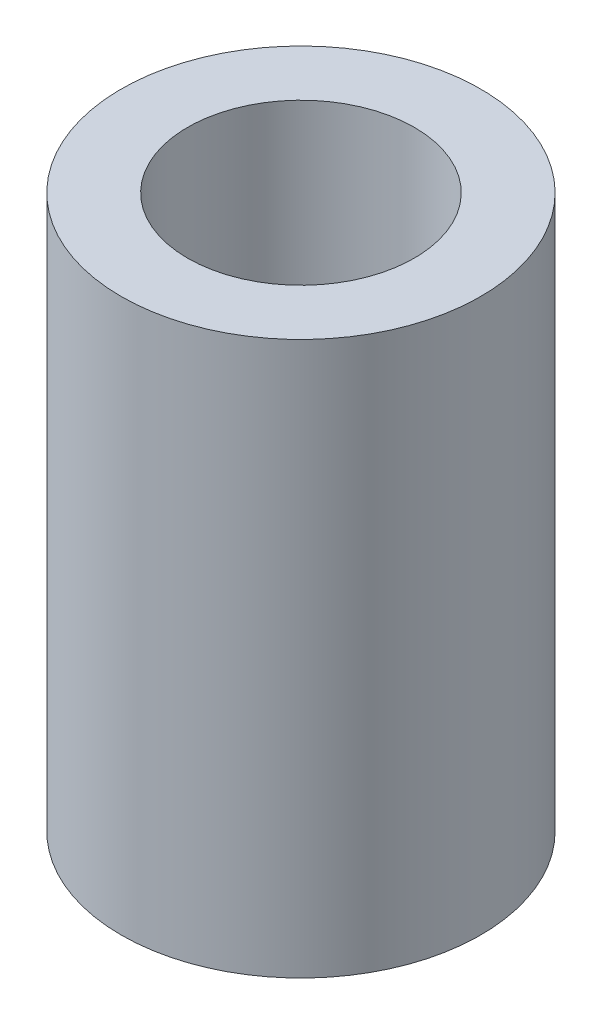
SolidWorks part; units mm, degrees
ref_plane "Спереди" through (0, 0, 0) normal (0, 0, 1) x (1, 0, 0)
ref_plane "Сверху" through (0, 0, 0) normal (0, 1, 0) x (1, 0, 0)
ref_plane "Справа" through (0, 0, 0) normal (1, 0, 0) x (0, 0, -1)
sketch "Sketch1" plane through (0, 0, 0) normal (0, 1, 0) x (1, 0, 0)
  circle A0 centre (0, 0) radius 6.5
  circle A1 centre (0, 0) radius 4.1
  dimension "D1" = 8.2
  dimension "D2" = 13
extrude "Boss-Extrude1" add sketch "Sketch1" along normal blind 20
